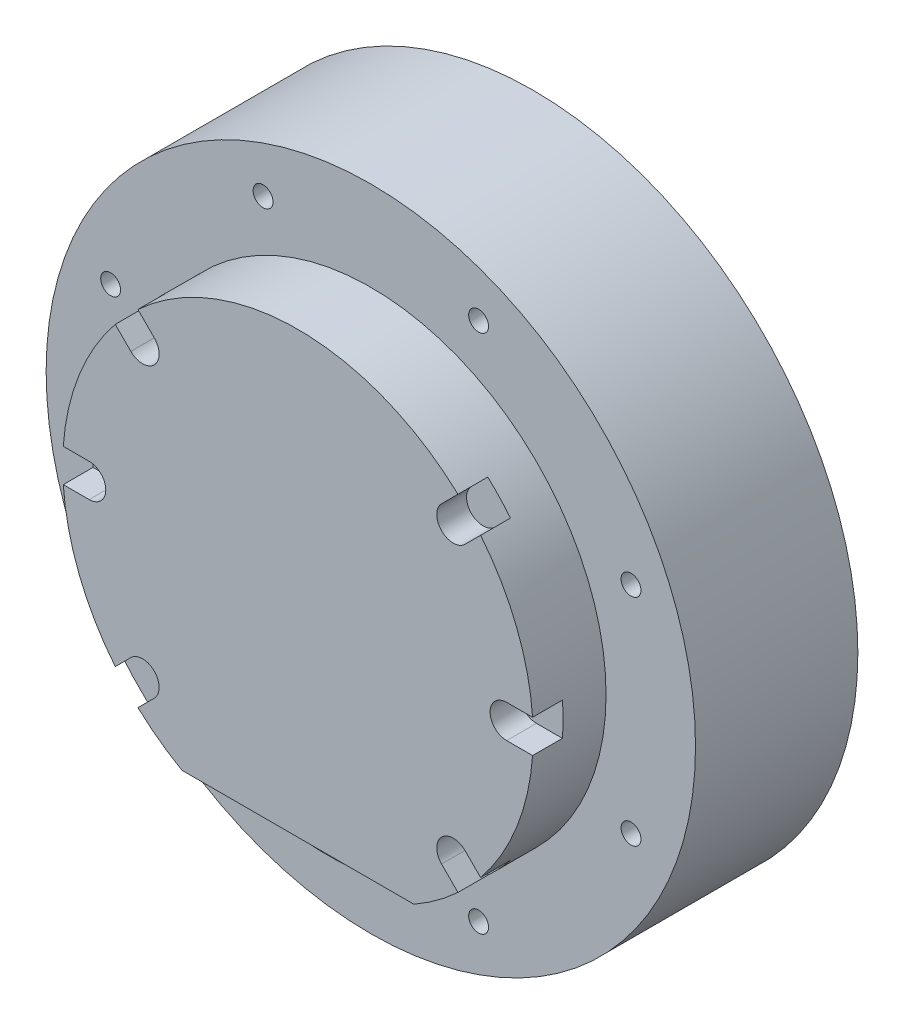
SolidWorks part; units mm, degrees
ref_plane "前视基准面" through (0, 0, 0) normal (0, 0, 1) x (1, 0, 0)
ref_plane "上视基准面" through (0, 0, 0) normal (0, 1, 0) x (1, 0, 0)
ref_plane "右视基准面" through (0, 0, 0) normal (1, 0, 0) x (0, 0, -1)
sketch "草图1" plane through (0, 0, 0) normal (0, 1, 0) x (1, 0, 0)
  line L0 (0, -11) -> (0, 37.8313)
  line L1 (0, 0) -> (49, 0)
  line L2 (0, 0) -> (0, 24.5)
  line L3 (0, 24.5) -> (49, 24.5)
  line L4 (49, 0) -> (49, 24.5)
  line L5 (0, 0) -> (35.5, 0)
  line L6 (0, 0) -> (0, -11)
  line L7 (0, -11) -> (35.5, -11)
  line L8 (35.5, 0) -> (35.5, -11)
  line L9 (0, 24.5) -> (24, 24.5)
  line L10 (0, 24.5) -> (0, 25.8)
  line L11 (0, 25.8) -> (24, 25.8)
  line L12 (24, 24.5) -> (24, 25.8)
  line L13 (0, 25.8) -> (18.5, 25.8)
  line L14 (0, 25.8) -> (0, 27.5)
  line L15 (0, 27.5) -> (18.5, 27.5)
  line L16 (18.5, 25.8) -> (18.5, 27.5)
  dimension "D1" = 49
  dimension "D2" = 35.5
  dimension "D3" = 11
  dimension "D4" = 24
  dimension "D5" = 18.5
  dimension "D6" = 1.3
  dimension "D7" = 3
  dimension "D8" = 38.5
revolve "旋转1" add sketch "草图1" angle 360 about L0
sketch "草图2" plane through (0, 0, -24.5) normal (0, 0, -1) x (-1, 0, 0)
  line L0 (0, 42.5) -> (0, -42.5) construction
  line L1 (0, 0) -> (16.264, 39.2649) construction
  circle A0 centre (0, 0) radius 42.5 construction
  circle A1 centre (16.264, 39.2649) radius 1.5
  circle A2 centre (-16.264, 39.2649) radius 1.5
  circle A3 centre (-39.2649, 16.264) radius 1.5
  circle A4 centre (-39.2649, -16.264) radius 1.5
  circle A5 centre (-16.264, -39.2649) radius 1.5
  circle A6 centre (16.264, -39.2649) radius 1.5
  circle A7 centre (39.2649, -16.264) radius 1.5
  circle A8 centre (39.2649, 16.264) radius 1.5
  point P24 (0, 0)
  dimension "D1" = 85
  dimension "D3" = 3
  dimension "D2" = 22.5
  dimension "D4" = 8
extrude "切除-拉伸1" cut sketch "草图2" against normal up to next
sketch "草图3" plane through (0, 0, 11) normal (0, 0, 1) x (1, 0, 0)
  line L0 (0, 35.5) -> (0, -35.5) construction
  line L1 (-35.5, 0) -> (35.5, 0) construction
  line L2 (-38.5, 0) -> (-31.5, 0) construction
  line L3 (-38.5, 2.5) -> (-31.5, 2.5)
  line L4 (-38.5, -2.5) -> (-31.5, -2.5)
  line L5 (-17.5, -30.8869) -> (17.5, -30.8869)
  line L7 (-28.3968, -26.7298) -> (-23.4471, -21.7801) construction
  line L8 (-30.1646, -24.9621) -> (-25.2148, -20.0123)
  line L9 (-26.629, -28.4976) -> (-21.6793, -23.5479)
  line L10 (28.3968, -26.7298) -> (23.4471, -21.7801) construction
  line L11 (30.1646, -24.9621) -> (25.2148, -20.0123)
  line L12 (26.629, -28.4976) -> (21.6793, -23.5479)
  line L13 (38.5, 0) -> (31.5, 0) construction
  line L14 (38.5, 2.5) -> (31.5, 2.5)
  line L15 (38.5, -2.5) -> (31.5, -2.5)
  line L16 (-28.3968, 26.7298) -> (-23.4471, 21.7801) construction
  line L17 (-30.1646, 24.9621) -> (-25.2148, 20.0123)
  line L18 (-26.629, 28.4976) -> (-21.6793, 23.5479)
  line L19 (28.3968, 26.7298) -> (23.4471, 21.7801) construction
  line L20 (30.1646, 24.9621) -> (25.2148, 20.0123)
  line L21 (26.629, 28.4976) -> (21.6793, 23.5479)
  circle A0 centre (0, 0) radius 35.5 construction
  circle A1 centre (0, 0) radius 35.5 construction
  arc A2 (-38.5, 2.5) -> (-38.5, -2.5) centre (-38.5, 0) ccw
  arc A3 (-31.5, -2.5) -> (-31.5, 2.5) centre (-31.5, 0) ccw
  arc A4 (-17.5, -30.8869) -> (17.5, -30.8869) centre (0, 0) ccw
  arc A5 (-30.1646, -24.9621) -> (-26.629, -28.4976) centre (-28.3968, -26.7298) ccw
  arc A6 (-21.6793, -23.5479) -> (-25.2148, -20.0123) centre (-23.4471, -21.7801) ccw
  arc A7 (30.1646, -24.9621) -> (26.629, -28.4976) centre (28.3968, -26.7298) cw
  arc A8 (21.6793, -23.5479) -> (25.2148, -20.0123) centre (23.4471, -21.7801) cw
  arc A9 (38.5, 2.5) -> (38.5, -2.5) centre (38.5, 0) cw
  arc A10 (31.5, -2.5) -> (31.5, 2.5) centre (31.5, 0) cw
  arc A11 (-30.1646, 24.9621) -> (-26.629, 28.4976) centre (-28.3968, 26.7298) cw
  arc A12 (-21.6793, 23.5479) -> (-25.2148, 20.0123) centre (-23.4471, 21.7801) cw
  arc A13 (30.1646, 24.9621) -> (26.629, 28.4976) centre (28.3968, 26.7298) ccw
  arc A14 (21.6793, 23.5479) -> (25.2148, 20.0123) centre (23.4471, 21.7801) ccw
  point P11 (-35, 0)
  point P21 (-25.9219, -24.255)
  point P29 (25.9219, -24.255)
  point P36 (35, 0)
  point P43 (-25.9219, 24.255)
  point P50 (25.9219, 24.255)
  point P54 (0, 0)
  dimension "D2" = 5
  dimension "D5" = 3
  dimension "D1" = 5
  dimension "D3" = 7
  dimension "D4" = 7
  dimension "D6" = 35.5
  dimension "D7" = 35.5
extrude "切除-拉伸3" cut sketch "草图3" against normal blind 4.5
sketch "草图4" plane through (0, 0, -27.5) normal (0, 0, -1) x (-1, 0, 0)
  line L0 (0, 0) -> (0, 14) construction
  line L1 (0, 0) -> (7, 12.1244)
  circle A0 centre (0, 0) radius 14 construction
  circle A1 centre (7, 12.1244) radius 2
  circle A2 centre (14, 0) radius 2
  circle A3 centre (7, -12.1244) radius 2
  circle A4 centre (-7, -12.1244) radius 2
  circle A5 centre (-14, 0) radius 2
  circle A6 centre (-7, 12.1244) radius 2
  circle A7 centre (0, 14) radius 1.5
  circle A8 centre (0, -14) radius 1.5
  point P19 (0, 0)
  dimension "D1" = 28
  dimension "D3" = 4
  dimension "D5" = 3
  dimension "D6" = 3
  dimension "D2" = 30
  dimension "D4" = 6
extrude "切除-拉伸4" cut sketch "草图4" against normal blind 5
sketch "Sketch1" plane through (0, 0, 11) normal (0, 0, 1) x (1, 0, 0)
  circle A0 centre (0, 0) radius 18
